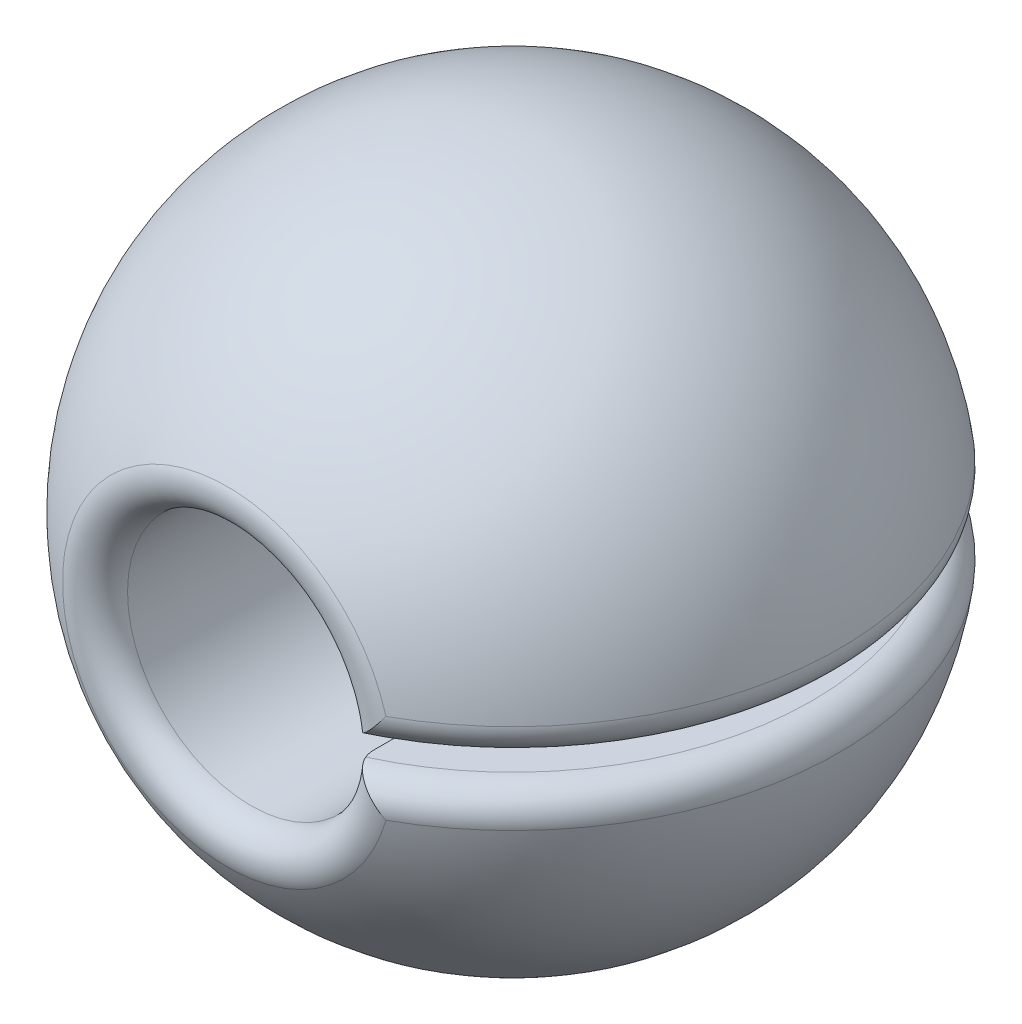
SolidWorks part; units mm, degrees
ref_plane "정면" through (0, 0, 0) normal (0, 0, 1) x (1, 0, 0)
ref_plane "윗면" through (0, 0, 0) normal (0, 1, 0) x (1, 0, 0)
ref_plane "우측면" through (0, 0, 0) normal (1, 0, 0) x (0, 0, -1)
sketch "스케치1" plane through (0, 0, 0) normal (0, 0, 1) x (1, 0, 0)
  line L0 (0, 11.7897) -> (0, -13.2661) construction
  line L1 (0, 12) -> (0, -12)
  arc A0 (0, 12) -> (0, -12) centre (0, 0) ccw
  dimension "D1" = 24
revolve "회전2" add sketch "스케치1" angle 360 about L0
sketch "스케치2" plane through (0, 0, 0) normal (0, 0, 1) x (1, 0, 0)
  circle A1 centre (0, 0) radius 4.5
  dimension "D1" = 9
extrude "컷-돌출1" cut sketch "스케치2" against normal mid plane 30 contours A1
sketch "스케치3" plane through (0, 0, 0) normal (0, 0, 1) x (1, 0, 0)
  line L1 (2.0918, 0.5) -> (16.7984, 0.5)
  line L2 (2.0918, 0.5) -> (2.0918, -0.5)
  line L3 (2.0918, -0.5) -> (16.7984, -0.5)
  line L4 (16.7984, 0.5) -> (16.7984, -0.5)
  point P4 (2.0918, 0)
  dimension "D1" = 1
extrude "컷-돌출2" cut sketch "스케치3" against normal mid plane 46
fillet "필렛1" radius 1 4 edges at (-4.5, 0, -11.1243) (-4.5, 0, 11.1243) (11.9896, 0.5, 0) (11.9896, -0.5, 0)
ref_point "점1"
